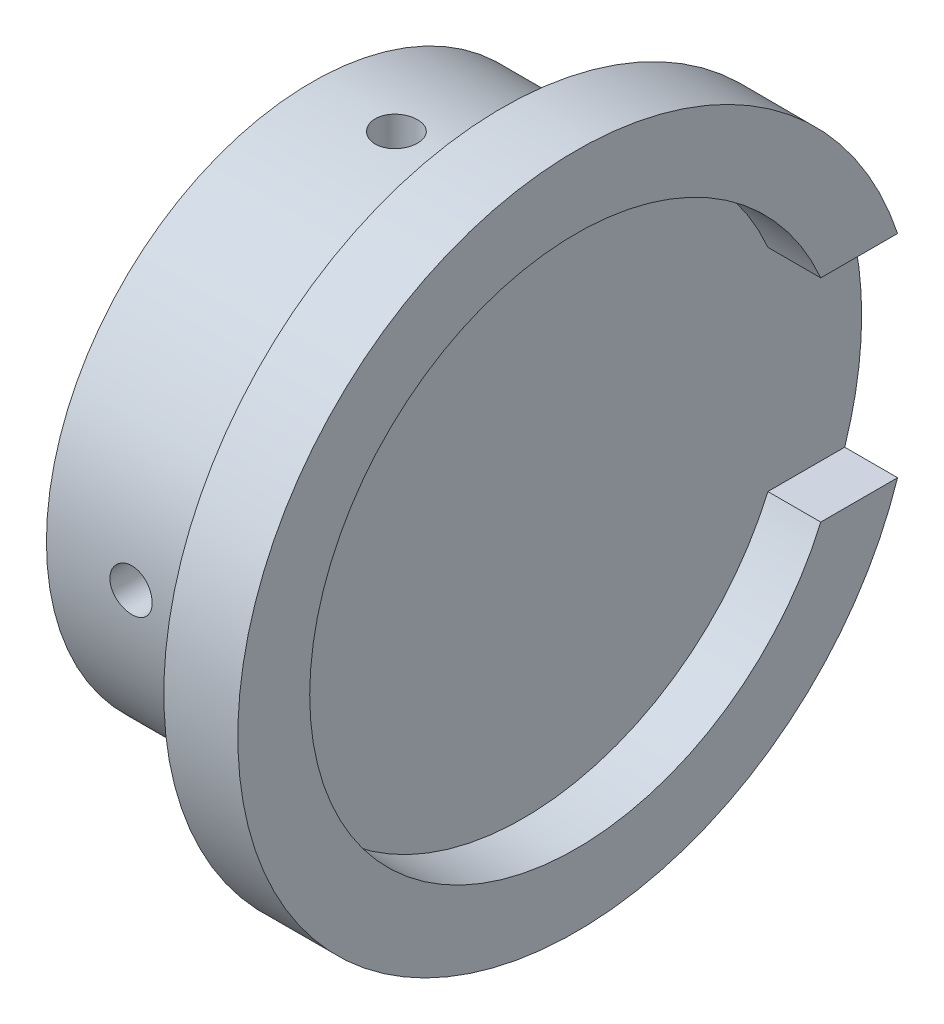
SolidWorks part; units mm, degrees
ref_plane "前视基准面" through (0, 0, 0) normal (0, 0, 1) x (1, 0, 0)
ref_plane "上视基准面" through (0, 0, 0) normal (0, 1, 0) x (1, 0, 0)
ref_plane "右视基准面" through (0, 0, 0) normal (1, 0, 0) x (0, 0, -1)
other "Configuration Table"
sketch "草图1" plane through (0, 0, 0) normal (1, 0, 0) x (0, 0, -1)
  circle A0 centre (0, 0) radius 12.55
  dimension "D1" = 25.1
extrude "凸台-拉伸1" add sketch "草图1" along normal blind 10
sketch "草图2" plane through (0, 0, 0) normal (-1, 0, 0) x (0, 0, 1)
  circle A0 centre (0, 0) radius 3
  dimension "D1" = 6
extrude "切除-拉伸1" cut sketch "草图2" against normal blind 7
sketch "草图3" plane through (0, 0, 0) normal (0, 1, 0) x (1, 0, 0)
  line L0 (0, 12.55) -> (0, -12.55) construction
  circle A0 centre (4, 0) radius 1
  dimension "D1" = 2
  dimension "D2" = 4
extrude "切除-拉伸2" cut sketch "草图3" against normal up to next and the other way up to next
sketch "草图4" plane through (0, 0, 0) normal (0, 0, 1) x (1, 0, 0)
  line L1 (0, 12.55) -> (0, -12.55) construction
  circle A0 centre (4, 0) radius 1
  dimension "D2" = 2
  dimension "D1" = 4
extrude "切除-拉伸3" cut sketch "草图4" against normal blind 19 and the other way blind 21
sketch "草图5" plane through (10, 0, 0) normal (1, 0, 0) x (0, 0, -1)
  circle A0 centre (0, 0) radius 16
  dimension "D1" = 32
extrude "凸台-拉伸2" add sketch "草图5" along normal blind 2.5 and the other way blind 1
sketch "草图6" plane through (12.5, 0, 0) normal (1, 0, 0) x (0, 0, -1)
  circle A0 centre (0, 0) radius 12.6
  dimension "D1" = 25.2
extrude "切除-拉伸4" cut sketch "草图6" against normal blind 2.5
fillet "圆角1" radius 2 1 edges at (9, 0, -12.55)
sketch "草图7" plane through (0, 0, 0) normal (0, 0, 1) x (1, 0, 0)
  line L0 (0, 0) -> (12.5, 0) construction
  line L7 (0, 12.55) -> (0, -12.55) construction
  line L8 (12.5, -16) -> (12.5, 16) construction
  line L10 (12.5, 5) -> (10, 5)
  line L11 (12.5, 5) -> (12.5, -5)
  line L12 (12.5, -5) -> (10, -5)
  line L13 (10, 5) -> (10, -5)
  dimension "D1" = 2.5
  dimension "D2" = 10
  dimension "D3" = 5
extrude "切除-拉伸5" cut sketch "草图7" against normal blind 21.5
ref_plane "基准面1" through (0, 0, 6) normal (0, 0, 1) x (1, 0, 0)
sketch "草图9" plane through (0, 0, 6) normal (0, 0, 1) x (1, 0, 0)
  line L1 (4, 2.3094) -> (2, 1.1547)
  line L2 (2, 1.1547) -> (2, -1.1547)
  line L3 (2, -1.1547) -> (4, -2.3094)
  line L4 (4, -2.3094) -> (6, -1.1547)
  line L5 (6, -1.1547) -> (6, 1.1547)
  line L6 (6, 1.1547) -> (4, 2.3094)
  circle A0 centre (4, 0) radius 2 construction
  dimension "D1" = 4
ref_plane "基准面3" through (0, 6, 0) normal (0, 1, 0) x (1, 0, 0)
sketch "草图11" plane through (0, 6, 0) normal (0, 1, 0) x (1, 0, 0)
  line L1 (4, 2.3094) -> (2, 1.1547)
  line L2 (2, 1.1547) -> (2, -1.1547)
  line L3 (2, -1.1547) -> (4, -2.3094)
  line L4 (4, -2.3094) -> (6, -1.1547)
  line L5 (6, -1.1547) -> (6, 1.1547)
  line L6 (6, 1.1547) -> (4, 2.3094)
  circle A0 centre (4, 0) radius 2 construction
  dimension "D1" = 4
extrude "切除-拉伸7" cut sketch "草图11" along normal blind 1.5
sketch "草图13" plane through (0, 0, 0) normal (-1, 0, 0) x (0, 0, 1)
  line L0 (0, 12.55) -> (0, 0) construction
  line L1 (6.875, 6) -> (-6.875, 6) construction
  line L2 (-2.31, 7.5) -> (2.31, 7.5)
  line L3 (-2.31, 7.5) -> (-2.31, 6)
  line L4 (-2.31, 6) -> (2.31, 6)
  line L5 (2.31, 7.5) -> (2.31, 6)
  circle A0 centre (0, 0) radius 12.55 construction
  circle A1 centre (0, 0) radius 12.55 construction
  dimension "D1" = 4.62
  dimension "D2" = 2.31
  dimension "D3" = 1.5
extrude "切除-拉伸8" cut sketch "草图13" against normal blind 4
sketch "草图14" plane through (0, 0, 0) normal (-1, 0, 0) x (0, 0, 1)
  line L0 (6, -6.875) -> (6, 6.875) construction
  line L1 (6, 2.31) -> (7.5, 2.31)
  line L2 (6, 2.31) -> (6, -2.31)
  line L3 (6, -2.31) -> (7.5, -2.31)
  line L4 (7.5, 2.31) -> (7.5, -2.31)
  line L5 (0, 0) -> (12.55, 0) construction
  circle A0 centre (0, 0) radius 12.55 construction
  dimension "D1" = 4.62
  dimension "D2" = 2.31
  dimension "D3" = 1.5
extrude "切除-拉伸9" cut sketch "草图14" against normal blind 4
extrude "切除-拉伸10" cut sketch "草图9" along normal blind 1.5
mirror "镜向1" about plane through (0, 0, 0) normal (0, 0, 1) of "切除-拉伸10", "切除-拉伸9"
mirror "镜向2" about plane through (0, 0, 0) normal (0, 1, 0) of "切除-拉伸8", "切除-拉伸7"
